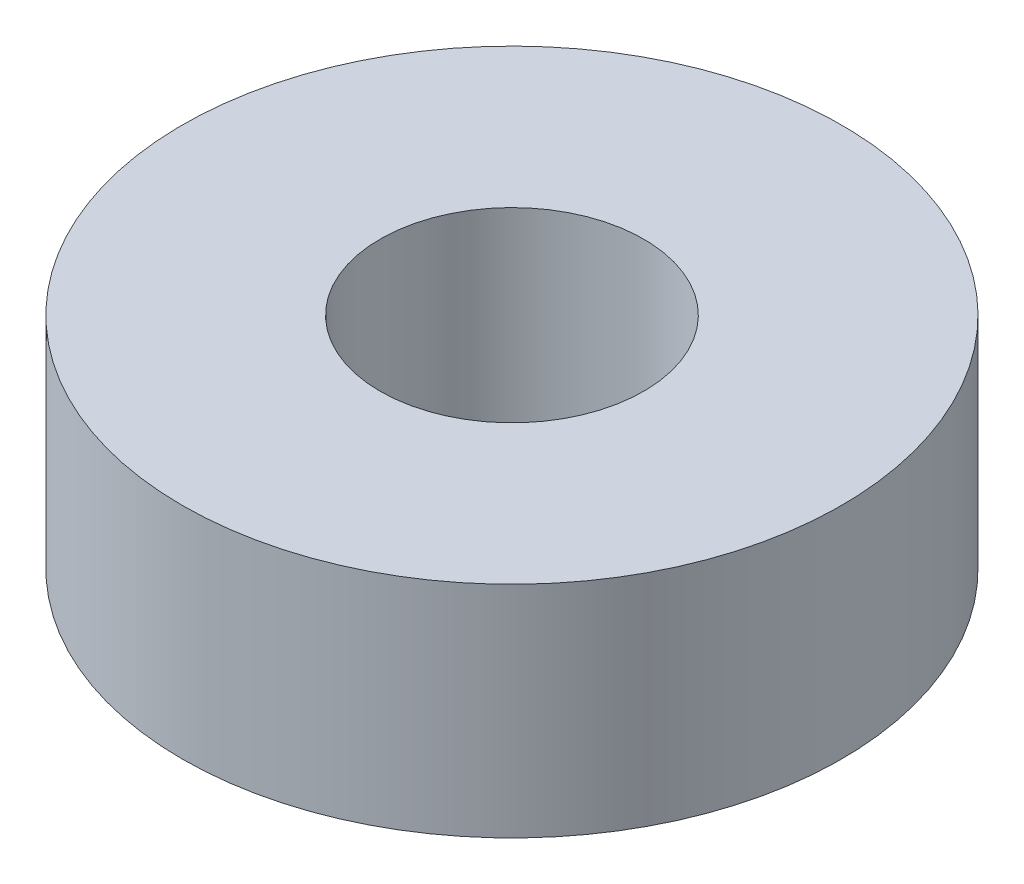
SolidWorks part; units mm, degrees
ref_plane "Płaszczyzna przednia" through (0, 0, 0) normal (0, 0, 1) x (1, 0, 0)
ref_plane "Płaszczyzna górna" through (0, 0, 0) normal (0, 1, 0) x (1, 0, 0)
ref_plane "Płaszczyzna prawa" through (0, 0, 0) normal (1, 0, 0) x (0, 0, -1)
sketch "Szkic1" plane through (0, 0, 0) normal (0, 1, 0) x (1, 0, 0)
  circle A0 centre (0, 0) radius 3
  circle A1 centre (0, 0) radius 7.5
  dimension "D1" = 6
  dimension "D2" = 15
extrude "Dodanie-wyciągnięcie1" add sketch "Szkic1" along normal blind 5
